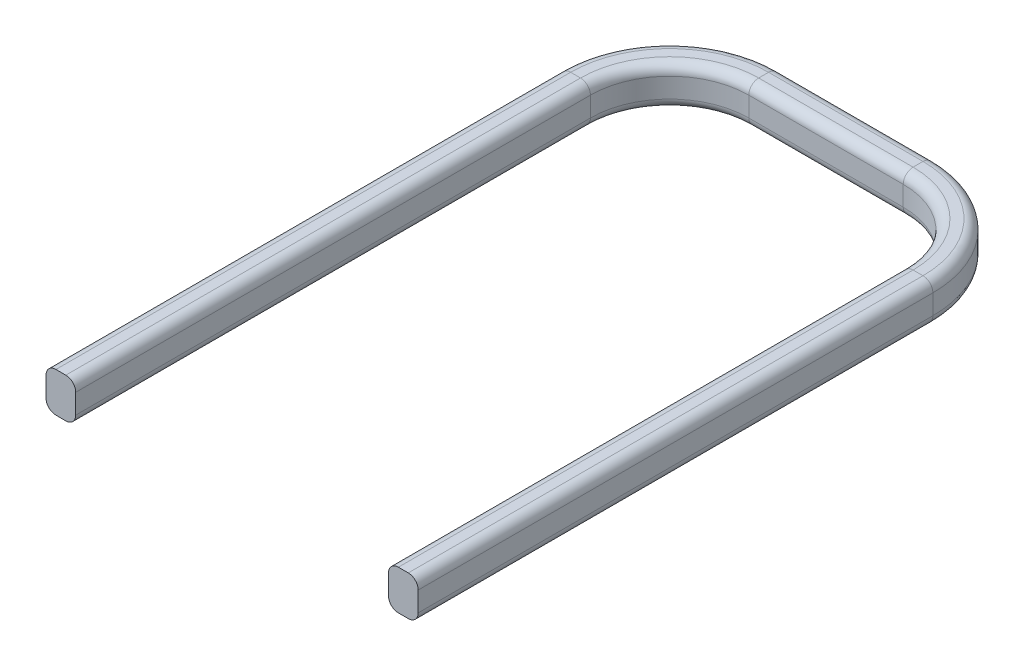
SolidWorks part; units mm, degrees
ref_plane "Front Plane" through (0, 0, 0) normal (0, 0, 1) x (1, 0, 0)
ref_plane "Top Plane" through (0, 0, 0) normal (0, 1, 0) x (1, 0, 0)
ref_plane "Right Plane" through (0, 0, 0) normal (1, 0, 0) x (0, 0, -1)
sketch "Sketch2" plane through (0, 0, 0) normal (0, 1, 0) x (1, 0, 0)
  line L2 (0, 0) -> (0, 13)
  line L3 (2, 15) -> (5.9, 15)
  line L4 (7.9, 0) -> (7.9, 13)
  arc A0 (5.9, 15) -> (7.9, 13) centre (5.9, 13) cw
  arc A1 (0, 13) -> (2, 15) centre (2, 13) cw
  point P9 (0, 15)
  dimension "D3" = 2
  dimension "D1" = 15
  dimension "D2" = 7.9
sketch "Sketch3" plane through (0, 0, 0) normal (0, 0, 1) x (1, 0, 0)
  line L1 (0, 0) -> (-0.75, 0)
  line L2 (0, 0) -> (0, 1)
  line L3 (0, 1) -> (-0.75, 1)
  line L4 (-0.75, 0) -> (-0.75, 1)
  dimension "D1" = 1
  dimension "D2" = 0.75
sweep "Sweep1" add profiles "Sketch3" path "Sketch2"
fillet "Fillet1" radius 0.25 20 edges at (7.9, 0, -6.5) (7.3142, 0, -14.4142) (3.95, 0, -15) (0.5858, 0, -14.4142) (8.65, 0, -6.5) (7.8445, 0, -14.9445) (3.95, 0, -15.75) (0.0555, 0, -14.9445) (7.9, 1, -6.5) (7.3142, 1, -14.4142) (3.95, 1, -15) (0.5858, 1, -14.4142) (8.65, 1, -6.5) (7.8445, 1, -14.9445) (3.95, 1, -15.75) (0.0555, 1, -14.9445) (0, 0, -6.5) (-0.75, 0, -6.5) (0, 1, -6.5) (-0.75, 1, -6.5)
